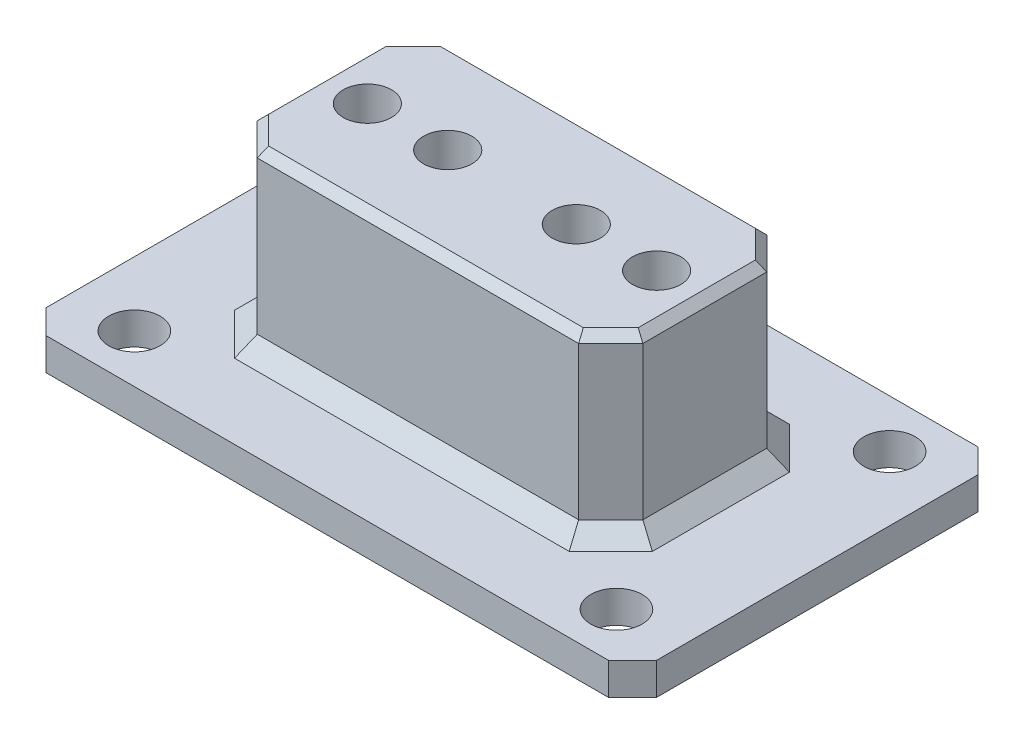
SolidWorks part; units mm, degrees
ref_plane "前视基准面" through (0, 0, 0) normal (0, 0, 1) x (1, 0, 0)
ref_plane "上视基准面" through (0, 0, 0) normal (0, 1, 0) x (1, 0, 0)
ref_plane "右视基准面" through (0, 0, 0) normal (1, 0, 0) x (0, 0, -1)
sketch "Sketch1" plane through (0, 0, 0) normal (0, 1, 0) x (1, 0, 0)
  line L0 (0, 5.2893) -> (0, 0) construction
  line L1 (-19, 11.5) -> (19, 11.5)
  line L2 (-19, 11.5) -> (-19, -11.5)
  line L3 (-19, -11.5) -> (19, -11.5)
  line L4 (19, 11.5) -> (19, -11.5)
  line L5 (-19, 11.5) -> (19, -11.5) construction
  line L6 (-19, -11.5) -> (19, 11.5) construction
  line L7 (0, 0) -> (10.0249, 0) construction
  circle A0 centre (-15, 8.5) radius 1.6
  circle A1 centre (15, 8.5) radius 1.6
  circle A2 centre (15, -8.5) radius 1.6
  circle A3 centre (-15, -8.5) radius 1.6
  point P0 (0, 0)
  point P11 (10.0249, 0)
  dimension "D3" = 15
  dimension "D4" = 8.5
  dimension "D5" = 3.2
  dimension "D1" = 38
  dimension "D2" = 23
extrude "Boss-Extrude1" add sketch "Sketch1" along normal blind 2
sketch "Sketch2" plane through (0, 2, 0) normal (0, 1, 0) x (1, 0, 0)
  line L0 (0, 4.4823) -> (0, 0) construction
  line L1 (-12, 5.8542) -> (12, 5.8542)
  line L2 (-12, 5.8542) -> (-12, -5.8542)
  line L3 (-12, -5.8542) -> (12, -5.8542)
  line L4 (12, 5.8542) -> (12, -5.8542)
  line L5 (-12, 5.8542) -> (12, -5.8542) construction
  line L6 (-12, -5.8542) -> (12, 5.8542) construction
  circle A1 centre (15, -8.5) radius 1.6 construction
  circle A2 centre (-9, 0) radius 1.5
  circle A3 centre (-4, 0) radius 1.5
  circle A4 centre (4, 0) radius 1.5
  circle A5 centre (9, 0) radius 1.5
  point P0 (0, 0)
  point P14 (0, 0)
  point P15 (0, 0)
  dimension "D3" = 3
  dimension "D4" = 3
  dimension "D6" = 5
  dimension "D1" = 4
  dimension "D2" = 24
  dimension "D5" = 3
extrude "Boss-Extrude2" add sketch "Sketch2" along normal blind 11
chamfer "Chamfer1" distance 2 angle 45 4 edges at (-12, 7.5, 5.8542) (-12, 7.5, -5.8542) (12, 7.5, -5.8542) (12, 7.5, 5.8542)
chamfer "Chamfer2" distance 1 angle 45 8 edges at (0, 2, -5.8542) (11, 2, -4.8542) (12, 2, 0) (11, 2, 4.8542) (-11, 2, -4.8542) (-12, 2, 0) (-11, 2, 4.8542) (0, 2, 5.8542)
chamfer "Chamfer3" distance 1.5 angle 45 4 edges at (19, 1, -11.5) (19, 1, 11.5) (-19, 1, 11.5) (-19, 1, -11.5)
chamfer "Chamfer4" distance 0.5 angle 45 8 edges at (11, 13, 4.8542) (12, 13, 0) (11, 13, -4.8542) (0, 13, -5.8542) (-11, 13, -4.8542) (-12, 13, 0) (-11, 13, 4.8542) (0, 13, 5.8542)
